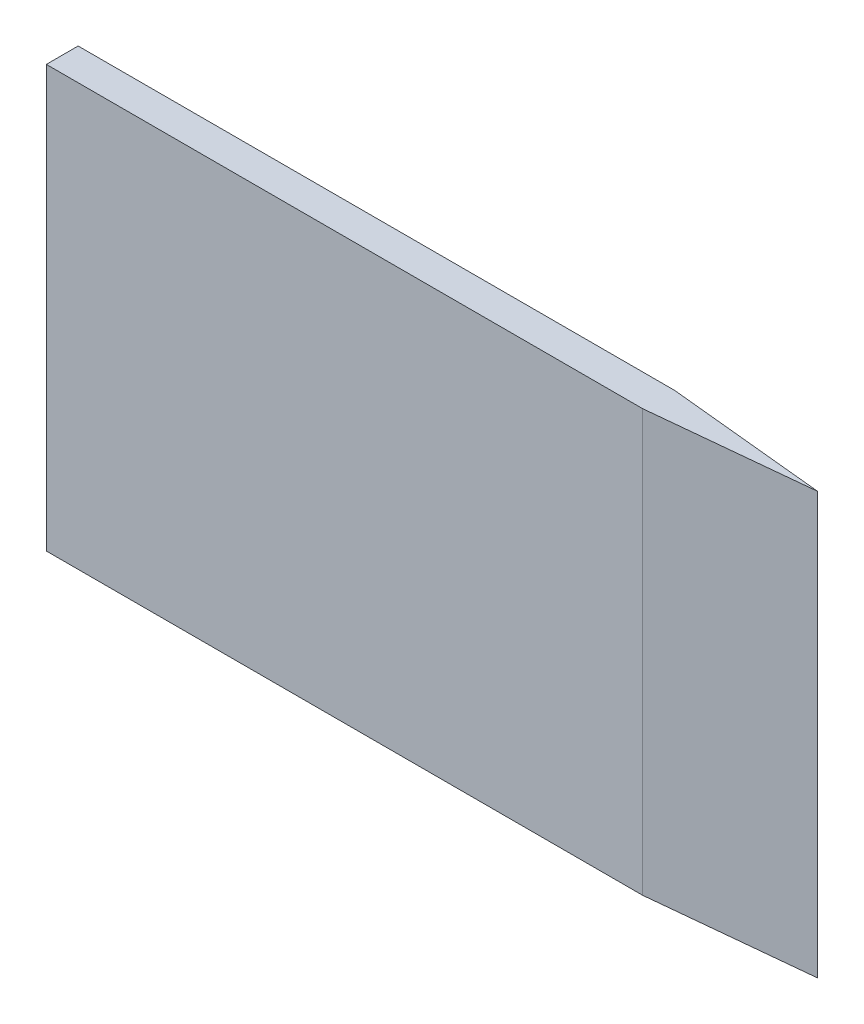
SolidWorks part; units mm, degrees
material "45钢"
ref_plane "前视基准面" through (0, 0, 0) normal (0, 0, 1) x (1, 0, 0)
ref_plane "上视基准面" through (0, 0, 0) normal (0, 1, 0) x (1, 0, 0)
ref_plane "右视基准面" through (0, 0, 0) normal (1, 0, 0) x (0, 0, -1)
sketch "草图1" plane through (0, 0, 0) normal (0, 0, 1) x (1, 0, 0)
  line L1 (-47.5, -26.5) -> (47.5, -26.5)
  line L2 (-47.5, -26.5) -> (-47.5, 26.5)
  line L3 (-47.5, 26.5) -> (47.5, 26.5)
  line L4 (47.5, -26.5) -> (47.5, 26.5)
  line L5 (-47.5, -26.5) -> (47.5, 26.5) construction
  line L6 (-47.5, 26.5) -> (47.5, -26.5) construction
  point P0 (0, 0)
  dimension "D1" = 53
  dimension "D2" = 95
extrude "凸台-拉伸1" add sketch "草图1" along normal mid plane 4
sketch "草图2" plane through (0, 0, 0) normal (0, 1, 0) x (1, 0, 0)
  line L0 (47.5, 0) -> (27.5, 2)
  line L1 (47.5, -2) -> (47.5, 2) construction
  line L2 (47.5, 2) -> (-47.5, 2) construction
  line L3 (47.5, 0) -> (27.5, -2)
  line L4 (47.5, -2) -> (-47.5, -2) construction
  dimension "D1" = 2
  dimension "D2" = 20
extrude "切除-拉伸1" cut sketch "草图2" against normal through all and the other way through all
